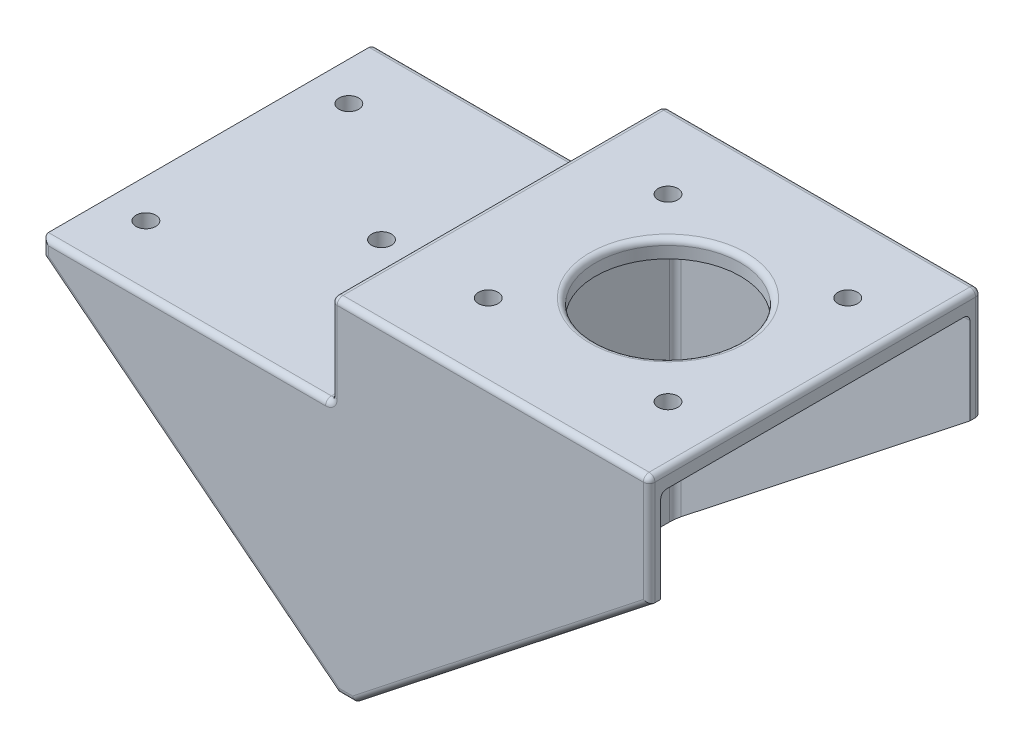
SolidWorks part; units mm, degrees
ref_plane "Front Plane" through (0, 0, 0) normal (0, 0, 1) x (1, 0, 0)
ref_plane "Top Plane" through (0, 0, 0) normal (0, 1, 0) x (1, 0, 0)
ref_plane "Right Plane" through (0, 0, 0) normal (1, 0, 0) x (0, 0, -1)
sketch "Sketch1" plane through (0, 0, 0) normal (0, 1, 0) x (1, 0, 0)
  line L1 (-52.3, 28.65) -> (52.3, 28.65)
  line L2 (-52.3, 28.65) -> (-52.3, -28.65)
  line L3 (-52.3, -28.65) -> (52.3, -28.65)
  line L4 (52.3, 28.65) -> (52.3, -28.65)
  line L5 (-52.3, 28.65) -> (52.3, -28.65) construction
  line L6 (-52.3, -28.65) -> (52.3, 28.65) construction
  point P0 (0, 0)
  dimension "D1" = 57.3
  dimension "D2" = 104.6
extrude "Boss-Extrude1" add sketch "Sketch1" along normal blind 3
sketch "Sketch3" plane through (0, 0, 0) normal (0, -1, 0) x (1, 0, 0)
  line L0 (-52.3, 28.65) -> (52.3, 28.65) construction
  line L1 (-1.5, 28.65) -> (1.5, 28.65)
  line L2 (-1.5, 28.65) -> (-1.5, -28.65)
  line L3 (-1.5, -28.65) -> (1.5, -28.65)
  line L4 (1.5, 28.65) -> (1.5, -28.65)
  line L5 (-1.5, 28.65) -> (1.5, -28.65) construction
  line L6 (-1.5, -28.65) -> (1.5, 28.65) construction
  line L7 (52.3, -28.65) -> (-52.3, -28.65) construction
  point P4 (0, 0)
  dimension "D1" = 3
extrude "Boss-Extrude3" add sketch "Sketch3" along normal blind 40
hole_wizard "M3 Clearance Hole1" positions "Sketch5" profile "Sketch6" hole size "M3" standard "ANSI Metric" end condition through all
sketch "Sketch5" plane through (0, 0, 0) normal (0, -1, 0) x (-1, 0, 0)
  line L1 (-42.4, 15.5) -> (-11.4, 15.5)
  line L2 (-42.4, 15.5) -> (-42.4, -15.5)
  line L3 (-42.4, -15.5) -> (-11.4, -15.5)
  line L4 (-11.4, 15.5) -> (-11.4, -15.5)
  line L5 (-42.4, 15.5) -> (-11.4, -15.5) construction
  line L6 (-42.4, -15.5) -> (-11.4, 15.5) construction
  line L7 (-52.3, -28.65) -> (-1.5, -28.65) construction
  point P2 (-11.4, -15.5)
  point P13 (-42.4, 15.5)
  point P14 (-42.4, -15.5)
  point P15 (-11.4, 15.5)
  point P27 (-26.9, 0)
  point P44 (-26.9, -28.65)
  dimension "D1" = 31
sketch "Sketch6" plane through (11.4, 0, 15.5) normal (1, 0, 0) x (0, 0, -1)
  line L0 (0, 0) -> (0, 3)
  line L1 (0, 3) -> (1.7, 3)
  line L2 (1.7, 3) -> (1.7, 0)
  line L5 (1.7, 0) -> (0, 0)
  line L11 (0, -6.35) -> (0, 107.95) construction
  dimension "Thru Hole Dia." = 3.4
  dimension "Thru Hole Depth" = 3
sketch "Sketch10" plane through (0, 0, 28.65) normal (0, 0, 1) x (1, 0, 0)
  line L0 (-52.3, 0) -> (-1.5, -40)
  line L1 (1.5, -40) -> (52.3, 0)
  line L2 (-52.3, 0) -> (-1.5, 0)
  line L3 (-1.5, 0) -> (-1.5, -40)
  line L4 (1.5, 0) -> (52.3, 0)
  line L5 (1.5, -40) -> (1.5, 0)
extrude "Boss-Extrude4" add sketch "Sketch10" against normal blind 2
ref_plane "Plane1" through (0, 0, 0) normal (0, 0, -1) x (-1, 0, 0)
mirror "Mirror1" about plane through (0, 0, 0) normal (0, 0, -1) of "Boss-Extrude4"
sketch "Sketch11" plane through (0, 0, 0) normal (0, -1, 0) x (1, 0, 0)
  line L1 (11.4, -15.5) -> (42.4, 15.5) construction
  circle A0 centre (26.9, 0) radius 12.5
  dimension "D1" = 25
extrude "Cut-Extrude1" cut sketch "Sketch11" against normal through all
hole_wizard "M3 Clearance Hole3" positions "Sketch12" profile "Sketch13" hole size "M3" standard "ANSI Metric" end condition through all
sketch "Sketch12" plane through (0, 0, 0) normal (0, -1, 0) x (-1, 0, 0)
  line L1 (8.1618, 17.5) -> (45.6382, 17.5)
  line L2 (8.1618, 17.5) -> (8.1618, -17.5)
  line L3 (8.1618, -17.5) -> (45.6382, -17.5)
  line L4 (45.6382, 17.5) -> (45.6382, -17.5)
  line L5 (8.1618, 17.5) -> (45.6382, -17.5) construction
  line L6 (8.1618, -17.5) -> (45.6382, 17.5) construction
  line L8 (1.5, -26.65) -> (52.3, -26.65) construction
  point P2 (45.6382, -17.5)
  point P19 (8.1618, 17.5)
  point P20 (8.1618, -17.5)
  point P21 (45.6382, 17.5)
  point P25 (26.9, 0)
  point P53 (26.9, -26.65)
  dimension "D1" = 35
sketch "Sketch13" plane through (-45.6382, 0, 17.5) normal (1, 0, 0) x (0, 0, -1)
  line L0 (0, 0) -> (0, 3)
  line L1 (0, 3) -> (1.7, 3)
  line L2 (1.7, 3) -> (1.7, 0)
  line L5 (1.7, 0) -> (0, 0)
  line L11 (0, -6.35) -> (0, 107.95) construction
  dimension "Thru Hole Dia." = 3.4
  dimension "Thru Hole Depth" = 3
sketch "Sketch14" plane through (0, 3, 0) normal (0, 1, 0) x (1, 0, 0)
  circle A4 centre (-12.5, 0) radius 1.7 construction
  circle A5 centre (-22.5, 0) radius 1.7 construction
  circle A6 centre (-12.5, 0) radius 1.7
  circle A7 centre (-22.5, 0) radius 1.7
extrude "Cut-Extrude2" cut sketch "Sketch14" against normal through all
sketch "Sketch16" plane through (0, 3, 0) normal (0, 1, 0) x (1, 0, 0)
  line L0 (-52.3, -28.65) -> (52.3, -28.65) construction
  line L1 (52.3, 28.65) -> (1.5, 28.65)
  line L2 (52.3, 28.65) -> (52.3, -28.65)
  line L3 (52.3, -28.65) -> (1.5, -28.65)
  line L4 (1.5, 28.65) -> (1.5, -28.65)
  line L5 (52.3, 28.65) -> (1.5, -28.65) construction
  line L6 (52.3, -28.65) -> (1.5, 28.65) construction
  line L7 (1.5, 26.65) -> (1.5, -26.65) construction
  circle A0 centre (26.9, 0) radius 12.5 construction
  circle A1 centre (42.4, 15.5) radius 1.7 construction
  circle A2 centre (42.4, -15.5) radius 1.7 construction
  circle A3 centre (11.4, -15.5) radius 1.7 construction
  circle A4 centre (11.4, 15.5) radius 1.7 construction
  circle A5 centre (26.9, 0) radius 12.5
  circle A6 centre (42.4, 15.5) radius 1.7
  circle A7 centre (42.4, -15.5) radius 1.7
  circle A8 centre (11.4, -15.5) radius 1.7
  circle A9 centre (11.4, 15.5) radius 1.7
  point P4 (26.9, 0)
extrude "Boss-Extrude5" add sketch "Sketch16" along normal blind 16
sketch "Sketch17" plane through (0, 0, 0) normal (0, -1, 0) x (1, 0, 0)
  line L1 (1.5, 26.65) -> (52.3, 26.65)
  line L2 (1.5, 26.65) -> (1.5, -26.65)
  line L3 (1.5, -26.65) -> (52.3, -26.65)
  line L4 (52.3, 26.65) -> (52.3, -26.65)
  line L5 (1.5, 26.65) -> (52.3, -26.65) construction
  line L6 (1.5, -26.65) -> (52.3, 26.65) construction
  point P4 (26.9, 0)
extrude "Cut-Extrude3" cut sketch "Sketch17" against normal blind 16
sketch "Sketch18" plane through (1.5, 0, 0) normal (-1, 0, 0) x (0, 0, 1)
  line L1 (-28.65, 19) -> (28.65, 19)
  line L2 (-28.65, 19) -> (-28.65, 3)
  line L3 (-28.65, 3) -> (28.65, 3)
  line L4 (28.65, 19) -> (28.65, 3)
  line L5 (-28.65, 19) -> (28.65, 3) construction
  line L6 (-28.65, 3) -> (28.65, 19) construction
  point P4 (0, 11)
extrude "Boss-Extrude6" add sketch "Sketch18" along normal blind 4
fillet "Fillet1" radius 1 30 edges at (-2.5, 19, 0) (-2.5, 3, 0) (0, -40, 28.65) (-26.9, -20, 28.65) (-52.3, 1.5, 28.65) (-27.4, 3, 28.65) (-2.5, 11, 28.65) (24.9, 19, 28.65) (52.3, 9.5, 28.65) (26.9, -20, 28.65) (-52.3, 1.5, -28.65) (-26.9, -20, -28.65) (0, -40, -28.65) (26.9, -20, -28.65) (52.3, 9.5, -28.65) (24.9, 19, -28.65) (-2.5, 11, -28.65) (-27.4, 3, -28.65) (1.5, -12, 26.65) (1.5, -12, -26.65) (1.5, 16, 0) (26.9, 16, -26.65) (26.9, 16, 26.65) (-1.5, -20, 26.65) (-1.5, -20, -26.65) (-26.9, 0, -26.65) (-26.9, 0, 26.65) (-1.5, 0, 0) (52.3, 19, 0) (26.9, 19, 12.5)
